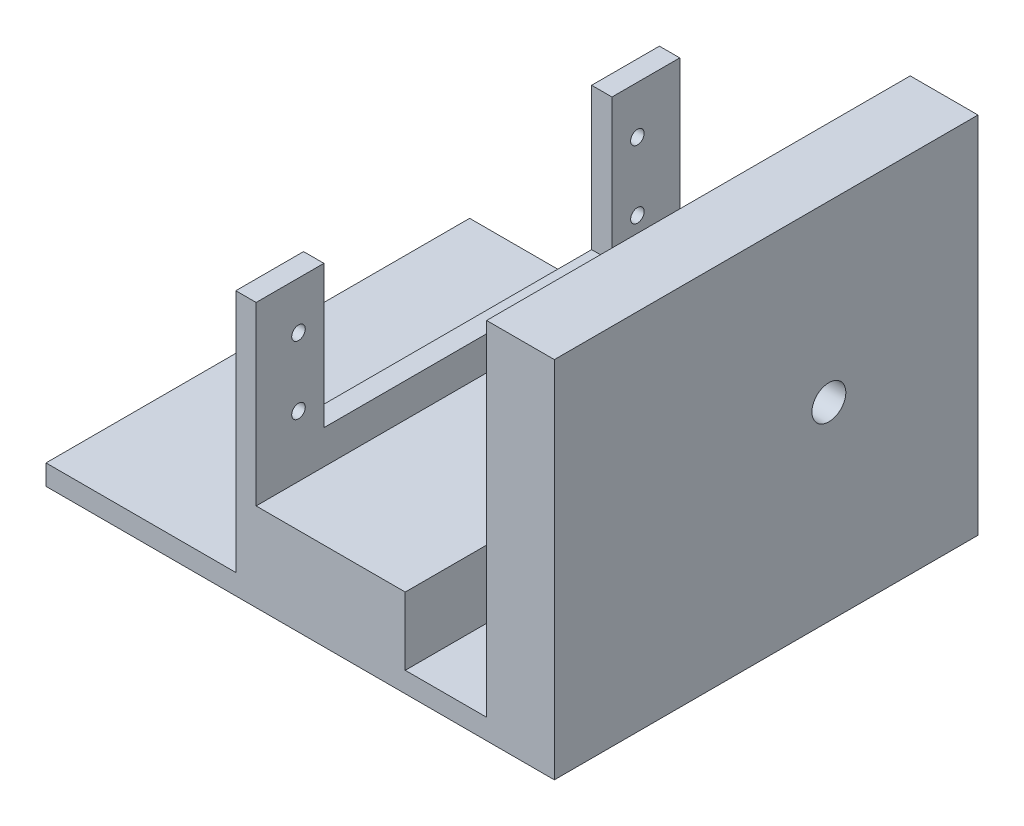
SolidWorks part; units mm, degrees
ref_plane "Front Plane" through (0, 0, 0) normal (0, 0, 1) x (1, 0, 0)
ref_plane "Top Plane" through (0, 0, 0) normal (0, 1, 0) x (1, 0, 0)
ref_plane "Right Plane" through (0, 0, 0) normal (1, 0, 0) x (0, 0, -1)
sketch "Sketch1" plane through (0, 0, 0) normal (0, 1, 0) x (1, 0, 0)
  line L1 (0, 0) -> (99, 0)
  line L2 (0, 0) -> (0, 62.5)
  line L3 (0, 62.5) -> (99, 62.5)
  line L4 (99, 0) -> (99, 62.5)
  dimension "D1" = 99
  dimension "D2" = 62.5
extrude "Boss-Extrude1" add sketch "Sketch1" along normal blind 53.7
sketch "Sketch2" plane through (0, 53.7, 0) normal (0, 1, 0) x (1, 0, 0)
  line L0 (99, 62.5) -> (0, 62.5) construction
  line L1 (10, 62.5) -> (89, 62.5)
  line L2 (10, 62.5) -> (10, 0)
  line L3 (10, 0) -> (89, 0)
  line L4 (89, 62.5) -> (89, 0)
  line L5 (0, 0) -> (99, 0) construction
  line L6 (0, 62.5) -> (0, 0) construction
  line L7 (99, 0) -> (99, 62.5) construction
  dimension "D1" = 10
  dimension "D2" = 10
extrude "Cut-Extrude1" cut sketch "Sketch2" against normal blind 50.7
sketch "Sketch3" plane through (0, 3, 0) normal (0, 1, 0) x (1, 0, 0)
  line L0 (89, 62.5) -> (10, 62.5) construction
  line L1 (77, 62.5) -> (52, 62.5)
  line L2 (77, 62.5) -> (77, 0)
  line L3 (77, 0) -> (52, 0)
  line L4 (52, 62.5) -> (52, 0)
  line L5 (10, 0) -> (89, 0) construction
  line L6 (89, 0) -> (89, 62.5) construction
  dimension "D1" = 12
  dimension "D2" = 25
extrude "Boss-Extrude2" add sketch "Sketch3" along normal blind 10
sketch "Sketch4" plane through (52, 0, 0) normal (-1, 0, 0) x (0, 0, 1)
  line L0 (-62.5, 13) -> (-62.5, 39)
  line L1 (-62.5, 53.7) -> (-62.5, 0) construction
  line L2 (-62.5, 39) -> (-52.5, 39)
  line L3 (-52.5, 39) -> (-52.5, 18)
  line L4 (-52.5, 18) -> (-10, 18)
  line L5 (-10, 18) -> (-10, 39)
  line L6 (-10, 39) -> (0, 39)
  line L7 (0, 53.7) -> (0, 0) construction
  line L8 (0, 39) -> (0, 13)
  line L9 (0, 13) -> (-62.5, 13)
  dimension "D1" = 10
  dimension "D2" = 10
  dimension "D3" = 26
  dimension "D4" = 26
  dimension "D5" = 21
extrude "Boss-Extrude4" add sketch "Sketch4" against normal blind 3
sketch "Sketch5" plane through (0, 0, 0) normal (0, -1, 0) x (1, 0, 0)
  line L1 (99, -62.5) -> (0, -62.5) construction
  line L2 (0, 0) -> (24, 0)
  line L3 (0, 0) -> (0, -62.5)
  line L4 (0, -62.5) -> (24, -62.5)
  line L6 (24, 0) -> (24, -62.5)
  line L7 (99, 0) -> (99, -62.5) construction
  dimension "D1" = 75
extrude "Cut-Extrude3" cut sketch "Sketch5" against normal blind 72
sketch "Sketch6" plane through (52, 0, 0) normal (-1, 0, 0) x (0, 0, 1)
  line L0 (-52.5, 39) -> (-62.5, 39) construction
  line L1 (0, 39) -> (-10, 39) construction
  line L2 (-10, 39) -> (-10, 18) construction
  line L3 (-52.5, 18) -> (-52.5, 39) construction
  circle A0 centre (-56.25, 32) radius 1
  circle A1 centre (-56.25, 22) radius 1
  circle A2 centre (-6.25, 22) radius 1
  circle A3 centre (-6.25, 32) radius 1
  point P8 (-57.5, 39)
  dimension "D1" = 2
  dimension "D2" = 2
  dimension "D3" = 2
  dimension "D4" = 2
  dimension "D5" = 10
  dimension "D6" = 10
  dimension "D7" = 7
  dimension "D8" = 7
  dimension "D9" = 3.75
  dimension "D10" = 3.75
  dimension "D11" = 3.75
  dimension "D12" = 3.75
extrude "Cut-Extrude4" cut sketch "Sketch6" against normal up to next
sketch "Sketch7" plane through (99, 0, 0) normal (1, 0, 0) x (0, 0, -1)
  line L0 (62.5, 53.7) -> (62.5, 0) construction
  line L1 (0, 0) -> (62.5, 0) construction
  circle A0 centre (40.5, 28) radius 2.5
  dimension "D3" = 5
  dimension "D1" = 22
  dimension "D2" = 28
extrude "Cut-Extrude5" cut sketch "Sketch7" against normal blind 72
sketch "Sketch8" plane through (99, 0, 0) normal (1, 0, 0) x (0, 0, -1)
  line L1 (0, 53.7) -> (62.5, 53.7)
  line L2 (0, 53.7) -> (0, 0)
  line L3 (0, 0) -> (62.5, 0)
  line L4 (62.5, 53.7) -> (62.5, 0)
  dimension "D1" = 53.7
  dimension "D2" = 62.5
sketch "Sketch9" plane through (52, 0, 0) normal (-1, 0, 0) x (0, 0, 1)
